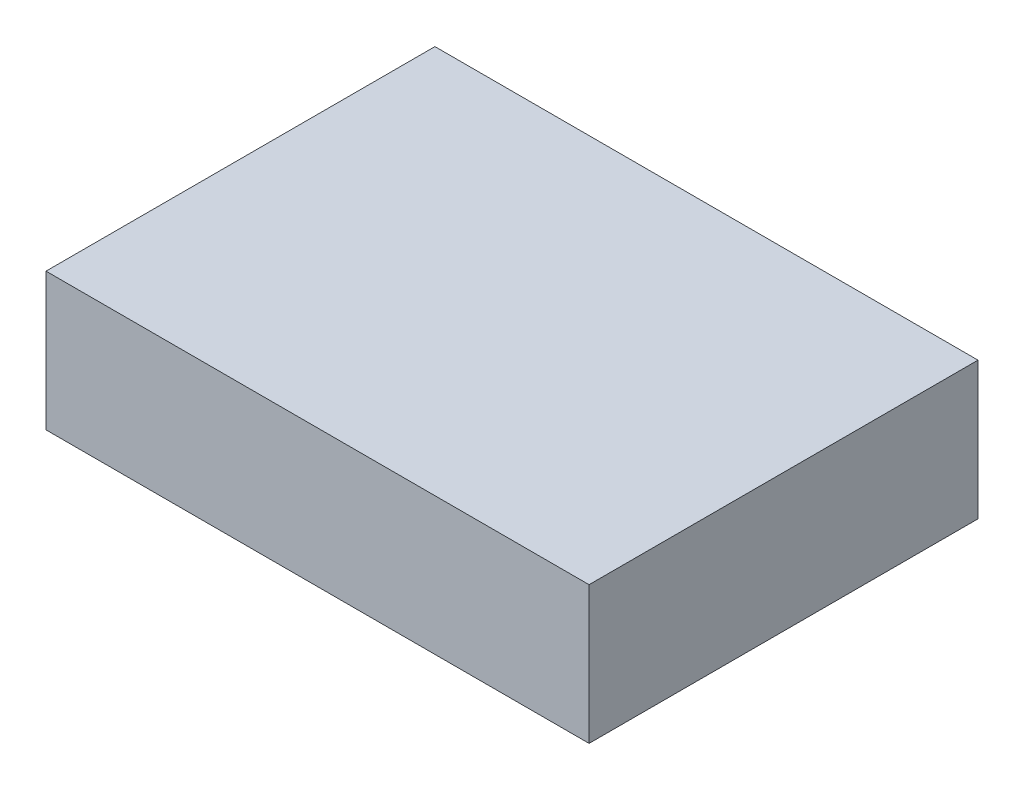
SolidWorks part; units mm, degrees
material "Cast Alloy Steel"
ref_plane "Front Plane" through (0, 0, 0) normal (0, 0, 1) x (1, 0, 0)
ref_plane "Top Plane" through (0, 0, 0) normal (0, 1, 0) x (1, 0, 0)
ref_plane "Right Plane" through (0, 0, 0) normal (1, 0, 0) x (0, 0, -1)
sketch "Sketch1" plane through (0, 0, 0) normal (0, 1, 0) x (1, 0, 0)
  line L1 (0, 0) -> (130.5543, 0)
  line L2 (0, 0) -> (0, 93.4974)
  line L3 (0, 93.4974) -> (130.5543, 93.4974)
  line L4 (130.5543, 0) -> (130.5543, 93.4974)
extrude "Boss-Extrude1" add sketch "Sketch1" along normal blind 33.046
